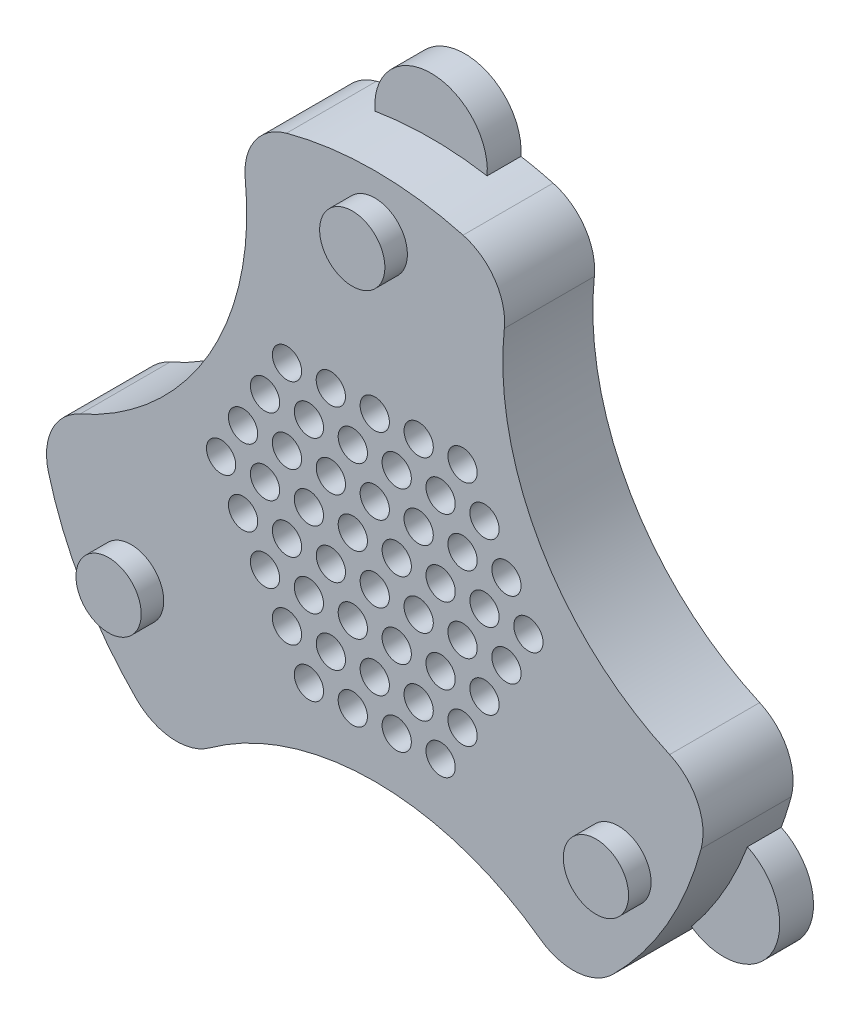
SolidWorks part; units mm, degrees
ref_plane "Спереди" through (0, 0, 0) normal (0, 0, 1) x (1, 0, 0)
ref_plane "Сверху" through (0, 0, 0) normal (0, 1, 0) x (1, 0, 0)
ref_plane "Справа" through (0, 0, 0) normal (1, 0, 0) x (0, 0, -1)
sketch "Sketch1" plane through (0, 0, 0) normal (0, 0, 1) x (1, 0, 0)
  line L0 (3.9, 6.755) -> (7.8, 0) construction
  line L2 (5.85, 10.1325) -> (11.7, 0) construction
  line L4 (7.8, 13.51) -> (15.6, 0) construction
  circle A61 centre (0, 0) radius 20
  circle A131 centre (0, 0) radius 1.25
  circle A484 centre (3.9, 0) radius 1.25
  circle A485 centre (7.8, 0) radius 1.25
  circle A486 centre (11.7, 0) radius 1.25
  circle A487 centre (15.6, 0) radius 1.25
  circle A488 centre (1.95, -3.3775) radius 1.25
  circle A489 centre (3.9, -6.755) radius 1.25
  circle A490 centre (5.85, -10.1325) radius 1.25
  circle A491 centre (7.8, -13.51) radius 1.25
  circle A492 centre (-1.95, -3.3775) radius 1.25
  circle A493 centre (-3.9, -6.755) radius 1.25
  circle A494 centre (-5.85, -10.1325) radius 1.25
  circle A495 centre (-7.8, -13.51) radius 1.25
  circle A496 centre (-3.9, 0) radius 1.25
  circle A497 centre (-7.8, 0) radius 1.25
  circle A498 centre (-11.7, 0) radius 1.25
  circle A499 centre (-15.6, 0) radius 1.25
  circle A500 centre (-1.95, 3.3775) radius 1.25
  circle A501 centre (-3.9, 6.755) radius 1.25
  circle A502 centre (-5.85, 10.1325) radius 1.25
  circle A503 centre (-7.8, 13.51) radius 1.25
  circle A504 centre (1.95, 3.3775) radius 1.25
  circle A505 centre (3.9, 6.755) radius 1.25
  circle A506 centre (5.85, 10.1325) radius 1.25
  circle A507 centre (7.8, 13.51) radius 1.25
  circle A508 centre (5.85, 3.3775) radius 1.25
  circle A509 centre (7.8, 6.755) radius 1.25
  circle A510 centre (9.75, 3.3775) radius 1.25
  circle A511 centre (11.7, 6.755) radius 1.25
  circle A512 centre (9.7491, 10.1341) radius 1.25
  circle A513 centre (13.6509, 3.3759) radius 1.25
  circle A514 centre (5.85, -3.3791) radius 1.25
  circle A515 centre (9.75, -3.3791) radius 1.25
  circle A516 centre (7.8, -6.7566) radius 1.25
  circle A517 centre (11.7, -6.7566) radius 1.25
  circle A518 centre (9.7491, -10.1356) radius 1.25
  circle A519 centre (13.6509, -3.3775) radius 1.25
  circle A520 centre (-0.0013, -6.7573) radius 1.25
  circle A521 centre (1.9487, -10.1348) radius 1.25
  circle A522 centre (-1.9513, -10.1348) radius 1.25
  circle A523 centre (-0.0013, -13.5123) radius 1.25
  circle A524 centre (-3.9032, -13.5123) radius 1.25
  circle A525 centre (3.9005, -13.5123) radius 1.25
  circle A526 centre (-5.8527, -3.3791) radius 1.25
  circle A527 centre (-7.8027, -6.7566) radius 1.25
  circle A528 centre (-9.7527, -3.3791) radius 1.25
  circle A529 centre (-11.7027, -6.7566) radius 1.25
  circle A530 centre (-13.6536, -3.3775) radius 1.25
  circle A531 centre (-9.7518, -10.1356) radius 1.25
  circle A532 centre (-5.8527, 3.3775) radius 1.25
  circle A533 centre (-9.7527, 3.3775) radius 1.25
  circle A534 centre (-7.8027, 6.755) radius 1.25
  circle A535 centre (-11.7027, 6.755) radius 1.25
  circle A536 centre (-9.7518, 10.1341) radius 1.25
  circle A537 centre (-13.6536, 3.3759) radius 1.25
  circle A538 centre (-0.0014, 6.7558) radius 1.25
  circle A539 centre (-1.9514, 10.1333) radius 1.25
  circle A540 centre (1.9486, 10.1333) radius 1.25
  circle A541 centre (-0.0014, 13.5108) radius 1.25
  circle A542 centre (3.9005, 13.5108) radius 1.25
  circle A543 centre (-3.9032, 13.5108) radius 1.25
  circle A544 centre (13.65, -1.1258) radius 2.2517 construction
  circle A545 centre (11.7009, -4.5044) radius 2.2522 construction
  circle A546 centre (9.75, -7.8834) radius 2.2522 construction
  circle A547 centre (7.7987, -11.2591) radius 2.2509 construction
  circle A548 centre (13.65, -1.1258) radius 0.65
  circle A549 centre (11.7009, -4.5044) radius 0.65
  circle A550 centre (9.75, -7.8834) radius 0.65
  circle A551 centre (7.7987, -11.2591) radius 0.65
  circle A552 centre (9.75, -1.1258) radius 0.65
  circle A553 centre (7.8009, -4.5044) radius 0.65
  circle A554 centre (5.85, -7.8834) radius 0.65
  circle A555 centre (3.8987, -11.2591) radius 0.65
  circle A556 centre (5.85, -1.1258) radius 0.65
  circle A557 centre (3.9009, -4.5044) radius 0.65
  circle A558 centre (1.95, -7.8834) radius 0.65
  circle A559 centre (-0.0013, -11.2591) radius 0.65
  circle A560 centre (1.95, -1.1258) radius 0.65
  circle A561 centre (0.0009, -4.5044) radius 0.65
  circle A562 centre (-1.95, -7.8834) radius 0.65
  circle A563 centre (-3.9013, -11.2591) radius 0.65
  circle A564 centre (-1.95, -1.1258) radius 0.65
  circle A565 centre (-3.8991, -4.5044) radius 0.65
  circle A566 centre (-5.85, -7.8834) radius 0.65
  circle A567 centre (-7.8013, -11.2591) radius 0.65
  circle A568 centre (-5.85, -1.1258) radius 0.65
  circle A569 centre (-7.7991, -4.5044) radius 0.65
  circle A570 centre (-9.75, -7.8834) radius 0.65
  circle A572 centre (-9.75, -1.1258) radius 0.65
  circle A573 centre (-11.6991, -4.5044) radius 0.65
  circle A576 centre (-13.65, -1.1258) radius 0.65
  circle A587 centre (0, 2.2517) radius 2.2517 construction
  circle A588 centre (0, 2.2517) radius 0.65
  circle A589 centre (3.9, 2.2517) radius 0.65
  circle A590 centre (7.8, 2.2517) radius 0.65
  circle A591 centre (11.7, 2.2517) radius 0.65
  circle A592 centre (15.6, 2.2517) radius 0.65
  circle A593 centre (1.9491, 5.6297) radius 2.2522 construction
  circle A594 centre (1.9491, 5.6297) radius 0.65
  circle A595 centre (5.8491, 5.6297) radius 0.65
  circle A596 centre (9.7491, 5.6297) radius 0.65
  circle A597 centre (13.6491, 5.6297) radius 0.65
  circle A598 centre (3.8991, 9.0072) radius 2.2522 construction
  circle A599 centre (3.8991, 9.0072) radius 0.65
  circle A600 centre (7.7991, 9.0072) radius 0.65
  circle A601 centre (11.6991, 9.0072) radius 0.65
  circle A602 centre (5.85, 12.3842) radius 2.2517 construction
  circle A603 centre (5.85, 12.3842) radius 0.65
  circle A604 centre (9.75, 12.3842) radius 0.65
  circle A605 centre (5.85, -14.6358) radius 0.65
  circle A606 centre (1.9509, -14.6353) radius 0.65
  circle A607 centre (-1.9491, -14.6353) radius 0.65
  circle A608 centre (-5.85, -14.6358) radius 0.65
  circle A609 centre (-15.6, 2.2517) radius 0.65
  circle A610 centre (-13.65, 5.6281) radius 0.65
  circle A611 centre (-11.7, 9.0056) radius 0.65
  circle A612 centre (-9.75, 12.3842) radius 0.65
  circle A613 centre (-5.85, 12.3842) radius 0.65
  circle A614 centre (-1.95, 12.3842) radius 0.65
  circle A615 centre (1.95, 12.3842) radius 0.65
  circle A616 centre (-7.8, 9.0056) radius 0.65
  circle A617 centre (-9.75, 5.6281) radius 0.65
  circle A618 centre (-11.7, 2.2517) radius 0.65
  circle A619 centre (-3.9, 9.0056) radius 0.65
  circle A620 centre (-5.85, 5.6281) radius 0.65
  circle A621 centre (-7.8, 2.2517) radius 0.65
  circle A622 centre (0, 9.0056) radius 0.65
  circle A623 centre (-1.95, 5.6281) radius 0.65
  circle A624 centre (-3.9, 2.2517) radius 0.65
  circle A625 centre (-15.5991, -4.5044) radius 0.65
  circle A626 centre (-13.65, -7.8834) radius 0.65
  circle A627 centre (-17.55, -7.8834) radius 0.65
  circle A628 centre (-19.5013, -11.2591) radius 0.65
  circle A629 centre (-15.6013, -11.2591) radius 0.65
  circle A630 centre (-11.7013, -11.2591) radius 0.65
  point P51 (0, 0)
  point P125 (-0.0013, -0.0008)
  point P231 (0, 0)
  dimension "D1" = 5
  dimension "D3" = 6
  dimension "D5" = 8
  dimension "D7" = 4
  dimension "D11" = 4
  dimension "D2" = 6
  dimension "D6" = 5
  dimension "D8" = 3
  dimension "D9" = 2
  dimension "D4" = 1.3
  dimension "D10" = 3
ref_plane "Plane1" through (0, 0, 10) normal (0, 0, 1) x (1, 0, 0)
sketch "Sketch2" plane through (0, 0, 10) normal (0, 0, 1) x (1, 0, 0)
  circle A63 centre (0, -2.2157) radius 1.3
  circle A64 centre (3.9, -2.2157) radius 1.3
  circle A65 centre (7.8, -2.2157) radius 1.3
  circle A92 centre (11.7, -2.2157) radius 1.3
  circle A103 centre (1.95, -5.5932) radius 1.3
  circle A107 centre (3.9, -8.9707) radius 1.3
  circle A136 centre (5.85, -12.3482) radius 1.3
  circle A138 centre (-1.95, -5.5932) radius 1.3
  circle A139 centre (-3.9, -8.9707) radius 1.3
  circle A140 centre (-5.85, -12.3482) radius 1.3
  circle A142 centre (-3.9, -2.2157) radius 1.3
  circle A143 centre (-7.8, -2.2157) radius 1.3
  circle A144 centre (-11.7, -2.2157) radius 1.3
  circle A146 centre (-1.95, 1.1618) radius 1.3
  circle A147 centre (-3.9, 4.5393) radius 1.3
  circle A148 centre (-5.85, 7.9168) radius 1.3
  circle A149 centre (-7.8, 11.2943) radius 1.3
  circle A150 centre (1.95, 1.1618) radius 1.3
  circle A151 centre (3.9, 4.5393) radius 1.3
  circle A152 centre (5.85, 7.9168) radius 1.3
  circle A153 centre (7.8, 11.2943) radius 1.3
  circle A154 centre (5.85, 1.1618) radius 1.3
  circle A155 centre (7.8, 4.5393) radius 1.3
  circle A156 centre (9.75, 1.1618) radius 1.3
  circle A157 centre (11.7, 4.5393) radius 1.3
  circle A158 centre (9.7491, 7.9183) radius 1.3
  circle A159 centre (13.6509, 1.1602) radius 1.3
  circle A160 centre (5.85, -5.5948) radius 1.3
  circle A161 centre (9.75, -5.5948) radius 1.3
  circle A162 centre (7.8, -8.9723) radius 1.3
  circle A166 centre (-0.0013, -8.9731) radius 1.3
  circle A167 centre (1.9487, -12.3506) radius 1.3
  circle A168 centre (-1.9513, -12.3506) radius 1.3
  circle A172 centre (-5.8527, -5.5948) radius 1.3
  circle A173 centre (-7.8027, -8.9723) radius 1.3
  circle A174 centre (-9.7527, -5.5948) radius 1.3
  circle A178 centre (-5.8527, 1.1618) radius 1.3
  circle A179 centre (-9.7527, 1.1618) radius 1.3
  circle A180 centre (-7.8027, 4.5393) radius 1.3
  circle A181 centre (-11.7027, 4.5393) radius 1.3
  circle A182 centre (-9.7518, 7.9183) radius 1.3
  circle A183 centre (-13.6536, 1.1602) radius 1.3
  circle A184 centre (-0.0014, 4.54) radius 1.3
  circle A185 centre (-1.9514, 7.9175) radius 1.3
  circle A186 centre (1.9486, 7.9175) radius 1.3
  circle A187 centre (-0.0014, 11.295) radius 1.3
  circle A188 centre (3.9005, 11.295) radius 1.3
  circle A189 centre (-3.9032, 11.295) radius 1.3
  circle A190 centre (0, 0) radius 16.85 construction
  circle A191 centre (0, 0) radius 19
  point P52 (0, -2.2157)
  point P126 (-0.0013, -2.2165)
  point P231 (0, -2.2157)
  dimension "D1" = 38
extrude "Boss-Extrude1" add sketch "Sketch2" along normal blind 8
sketch "Sketch3" plane through (0, 0, 18) normal (0, 0, 1) x (1, 0, 0)
  circle A0 centre (0, 0) radius 30
  circle A1 centre (0, 0) radius 17.488
extrude "Boss-Extrude2" add sketch "Sketch3" against normal blind 8
sketch "Sketch4" plane through (0, 0, 18) normal (0, 0, 1) x (1, 0, 0)
  circle A0 centre (0, 0) radius 25 construction
  circle A1 centre (0, 25) radius 2.9
  circle A2 centre (21.6506, -12.5) radius 2.9
  circle A3 centre (-21.6506, -12.5) radius 2.9
  point P11 (0, 0)
  dimension "D1" = 3
extrude "Boss-Extrude3" add sketch "Sketch4" along normal blind 2
sketch "Sketch6" plane through (0, 0, 10) normal (0, 0, -1) x (-1, 0, 0)
  circle A0 centre (0, 30) radius 5
  circle A1 centre (0, 0) radius 30 construction
  circle A2 centre (25.9808, -15) radius 5
  circle A3 centre (-25.9808, -15) radius 5
  circle A4 centre (0, 0) radius 30 construction
  point P5 (0, 30)
  point P10 (0, 0)
  point P12 (1.0017, 29.9833)
  point P13 (-1.4493, 29.965)
  point P14 (0, 0)
  point P15 (0, 30)
  point P16 (-0.8991, 29.9865)
  point P17 (0, 30)
  dimension "D1" = 3
extrude "Boss-Extrude4" add sketch "Sketch6" against normal blind 3
sketch "Sketch5" plane through (0, 0, 10) normal (0, 0, -1) x (-1, 0, 0)
  circle A0 centre (0, 25) radius 3
  circle A1 centre (21.6506, -12.5) radius 3
  circle A2 centre (-21.6506, -12.5) radius 3
extrude "Cut-Extrude1" cut sketch "Sketch5" against normal blind 3
sketch "Sketch7" plane through (0, 0, 10) normal (0, 0, -1) x (-1, 0, 0)
  line L0 (-36.3731, 21) -> (0, 0)
  line L8 (36.3731, 21) -> (0, 0)
  line L9 (0, -42) -> (0, 0)
  circle A1 centre (36.3731, 21) radius 25
  circle A3 centre (0, -42) radius 25
  circle A9 centre (0, 0) radius 42 construction
  circle A10 centre (-36.3731, 21) radius 25
  point P10 (0, 0)
  point P11 (0, 0)
  point P24 (0, 0)
  dimension "D1" = 3
extrude "Cut-Extrude2" cut sketch "Sketch7" against normal blind 8
fillet "Fillet2" radius 5 6 edges at (17.629, -24.2738, 14) (-17.629, -24.2738, 14) (-29.8362, -3.1303, 14) (-12.2072, 27.4041, 14) (12.2072, 27.4041, 14) (29.8362, -3.1303, 14)
